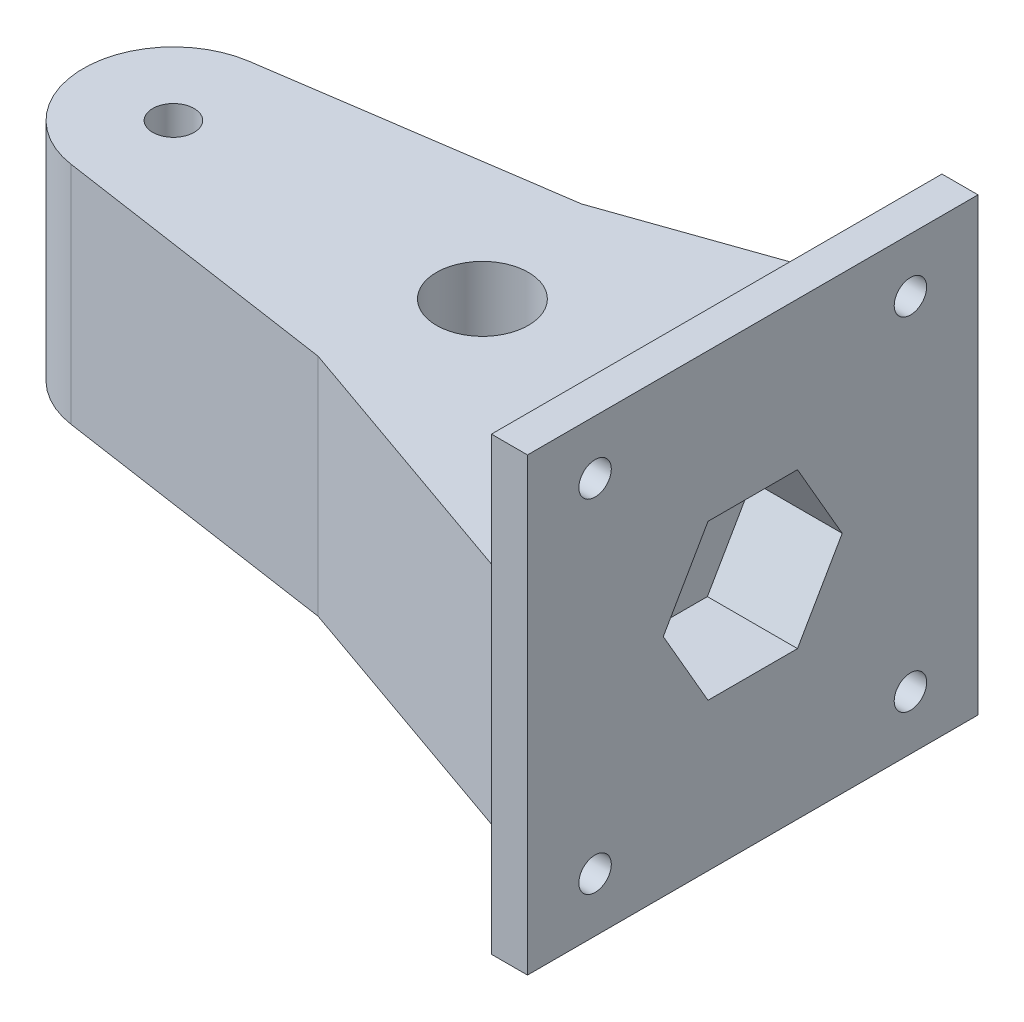
SolidWorks part; units mm, degrees
ref_plane "Front Plane" through (0, 0, 0) normal (0, 0, 1) x (1, 0, 0)
ref_plane "Top Plane" through (0, 0, 0) normal (0, 1, 0) x (1, 0, 0)
ref_plane "Right Plane" through (0, 0, 0) normal (1, 0, 0) x (0, 0, -1)
sketch "Sketch1" plane through (0, 0, 0) normal (0, 1, 0) x (1, 0, 0)
  line L4 (30, 12.5) -> (30, -12.5)
  line L5 (30, 12.5) -> (30, 25)
  line L6 (30, 25) -> (26, 25)
  line L12 (26, -25) -> (30, -25)
  line L14 (30, -25) -> (30, -12.5)
  line L16 (-3.6052, 14.6308) -> (26, 25)
  line L17 (-35.7577, 9.8932) -> (-3.6052, 14.6308)
  line L18 (-35.7577, -9.8932) -> (-3.6052, -14.6308)
  line L19 (25, 7.5) -> (15, 7.5) construction
  line L20 (25, 7.5) -> (25, -7.5) construction
  line L21 (25, -7.5) -> (15, -7.5) construction
  line L22 (15, 7.5) -> (15, -7.5) construction
  line L23 (20, -7.5) -> (20, 7.5) construction
  line L24 (25, 0) -> (15, 0) construction
  line L26 (26, -25) -> (-3.6052, -14.6308)
  circle A0 centre (0, 0) radius 5.1
  circle A1 centre (-34.3, 0) radius 2.3
  arc A2 (-35.7577, 9.8932) -> (-35.7577, -9.8932) centre (-34.3, 0) ccw
  circle A5 centre (0, 0) radius 15 construction
  point P0 (0, 0)
  point P9 (0, 0)
  point P16 (0, 0)
  point P655 (20, 0)
  dimension "D3" = 10.2
  dimension "D4" = 34.3
  dimension "D5" = 4.6
  dimension "D6" = 20
  dimension "D1" = 30
  dimension "D10" = 30
  dimension "D2" = 25
  dimension "D7" = 4
  dimension "D8" = 25
  dimension "D9" = 25
  dimension "D11" = 5
  dimension "D12" = 15
  dimension "D14" = 10
  dimension "D15" = 4
extrude "Boss-Extrude1" add sketch "Sketch1" along normal blind 25
sketch "Sketch3" plane through (30, 0, 0) normal (1, 0, 0) x (0, 0, -1)
  line L0 (-25, 25) -> (-25, 0) construction
  line L1 (-4.9652, 21.1) -> (-9.9304, 12.5)
  line L2 (-9.9304, 12.5) -> (-4.9652, 3.9)
  line L3 (-4.9652, 3.9) -> (4.9652, 3.9)
  line L4 (4.9652, 3.9) -> (9.9304, 12.5)
  line L5 (9.9304, 12.5) -> (4.9652, 21.1)
  line L6 (4.9652, 21.1) -> (-4.9652, 21.1)
  line L7 (-25, 25) -> (25, 25) construction
  circle A0 centre (0, 12.5) radius 8.6 construction
  point P1 (-25, 12.5)
  point P9 (0, 0)
  point P12 (0, 12.5)
  point P13 (3.5061, 18.5727)
  point P15 (0, 25)
  dimension "D1" = 17.2
sketch "Sketch4" plane through (30, 0, 0) normal (1, 0, 0) x (0, 0, -1)
  line L0 (25, 25) -> (25, 0) construction
  line L1 (-25, 25) -> (25, 25)
  line L2 (-25, 25) -> (-25, 37.5)
  line L3 (-25, 37.5) -> (25, 37.5)
  line L4 (25, 25) -> (25, 37.5)
  line L5 (0, 37.5) -> (0, 25) construction
  line L6 (-25, 31.25) -> (25, 31.25) construction
  line L7 (25, 0) -> (-25, 0)
  line L8 (25, 0) -> (25, -12.5)
  line L9 (25, -12.5) -> (-25, -12.5)
  line L10 (-25, 0) -> (-25, -12.5)
  line L11 (0, -12.5) -> (0, 0) construction
  line L12 (25, -6.25) -> (-25, -6.25) construction
  line L13 (-25, 25) -> (-25, 0) construction
  point P288 (0, 31.25)
  point P426 (0, -6.25)
  dimension "D1" = 50
extrude "Boss-Extrude3" add sketch "Sketch4" against normal blind 4
sketch "Sketch5" plane through (30, 0, 0) normal (1, 0, 0) x (0, 0, -1)
  line L0 (-25, 37.5) -> (-25, -12.5) construction
  line L1 (25, 37.5) -> (-25, 37.5) construction
  line L2 (-25, -12.5) -> (25, -12.5) construction
  line L3 (-25, 0) -> (-25, -12.5) construction
  line L4 (25, -12.5) -> (25, 0) construction
  line L5 (25, 25) -> (25, 37.5) construction
  line L6 (25, 37.5) -> (-25, 37.5) construction
  circle A0 centre (-17.5, 31.5) radius 1.8
  circle A1 centre (17.5, 31.5) radius 1.8
  circle A2 centre (17.5, -6.5) radius 1.8
  circle A3 centre (-17.5, -6.5) radius 1.8
  point P12 (-13.6216, -2.2098)
  dimension "D1" = 3.6
  dimension "D2" = 7.5
  dimension "D3" = 6
  dimension "D4" = 3.6
  dimension "D5" = 3.6
  dimension "D6" = 3.6
  dimension "D7" = 6
  dimension "D8" = 7.5
  dimension "D9" = 7.5
  dimension "D10" = 6
  dimension "D11" = 7.5
  dimension "D12" = 6
extrude "Cut-Extrude3" cut sketch "Sketch5" against normal through all both and the other way through all
extrude "Cut-Extrude4" cut sketch "Sketch3" against normal blind 10 and the other way through all
